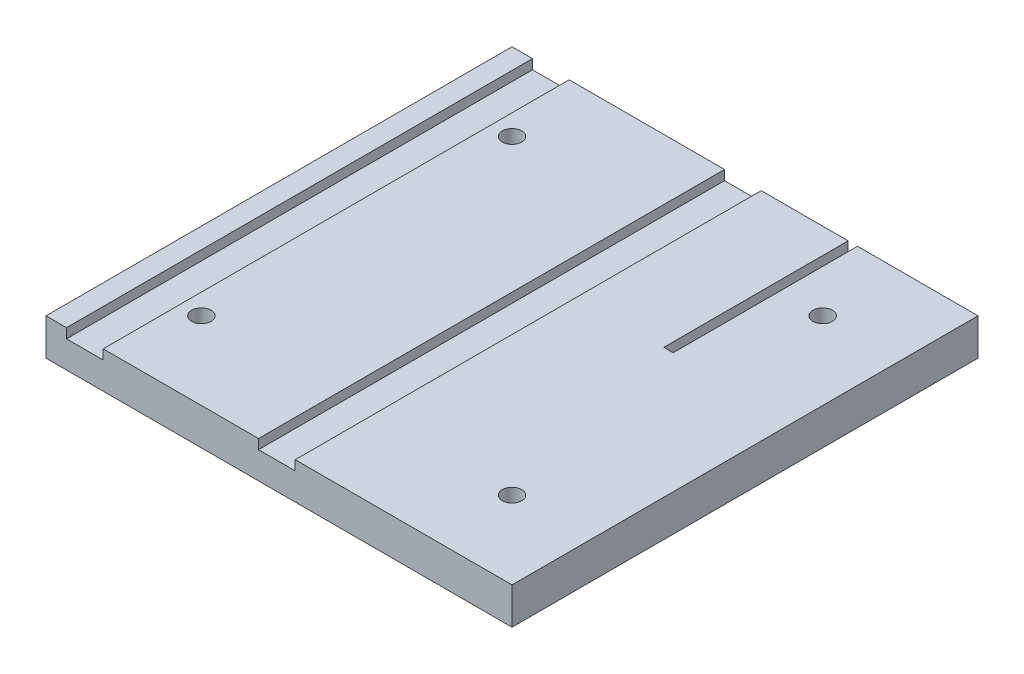
SolidWorks part; units mm, degrees
ref_plane "Front Plane" through (0, 0, 0) normal (0, 0, 1) x (1, 0, 0)
ref_plane "Top Plane" through (0, 0, 0) normal (0, 1, 0) x (1, 0, 0)
ref_plane "Right Plane" through (0, 0, 0) normal (1, 0, 0) x (0, 0, -1)
sketch "Sketch1" plane through (0, 0, 0) normal (0, 1, 0) x (1, 0, 0)
  line L1 (-76.2, 76.2) -> (76.2, 76.2)
  line L2 (-76.2, 76.2) -> (-76.2, -76.2)
  line L3 (-76.2, -76.2) -> (76.2, -76.2)
  line L4 (76.2, 76.2) -> (76.2, -76.2)
  line L5 (-76.2, 76.2) -> (76.2, -76.2) construction
  line L6 (-76.2, -76.2) -> (76.2, 76.2) construction
  circle A0 centre (-50.8, 50.8) radius 3.175
  circle A1 centre (50.8, 50.8) radius 3.175
  circle A2 centre (-50.8, -50.8) radius 3.175
  circle A3 centre (50.8, -50.8) radius 3.175
  point P0 (0, 0)
  dimension "D3" = 6.35
  dimension "D4" = 6.35
  dimension "D5" = 6.35
  dimension "D6" = 6.35
  dimension "D7" = 25.4
  dimension "D8" = 25.4
  dimension "D9" = 25.4
  dimension "D10" = 101.6
  dimension "D11" = 25.4
  dimension "D12" = 25.4
  dimension "D13" = 25.4
  dimension "D14" = 25.4
  dimension "D15" = 76.2
  dimension "D1" = 152.4
  dimension "D2" = 152.4
  dimension "D16" = 76.2
extrude "Boss-Extrude1" add sketch "Sketch1" along normal blind 12
sketch "Sketch2" plane through (0, 12, 0) normal (0, 1, 0) x (1, 0, 0)
  line L1 (-57.5, -76.2) -> (-69.5, -76.2)
  line L2 (-57.5, -76.2) -> (-57.5, 76.2)
  line L3 (-57.5, 76.2) -> (-69.5, 76.2)
  line L4 (-69.5, -76.2) -> (-69.5, 76.2)
  line L5 (-57.5, -76.2) -> (-69.5, 76.2) construction
  line L6 (-57.5, 76.2) -> (-69.5, -76.2) construction
  line L7 (-76.2, -76.2) -> (76.2, -76.2) construction
  line L9 (5.3, -76.2) -> (-6.7, -76.2)
  line L10 (5.3, -76.2) -> (5.3, 76.2)
  line L11 (5.3, 76.2) -> (-6.7, 76.2)
  line L12 (-6.7, -76.2) -> (-6.7, 76.2)
  line L13 (5.3, -76.2) -> (-6.7, 76.2) construction
  line L14 (5.3, 76.2) -> (-6.7, -76.2) construction
  line L15 (-76.2, 76.2) -> (-76.2, -76.2) construction
  line L17 (76.2, -76.2) -> (76.2, 76.2) construction
  line L18 (33.7325, 119.9745) -> (36.8088, 119.9745)
  line L19 (33.7325, 119.9745) -> (33.7325, 15.8925)
  line L20 (33.7325, 15.8925) -> (36.8088, 15.8925)
  line L21 (36.8088, 119.9745) -> (36.8088, 15.8925)
  line L22 (33.7325, 119.9745) -> (36.8088, 15.8925) construction
  line L23 (33.7325, 15.8925) -> (36.8088, 119.9745) construction
  point P0 (-63.5, 0)
  point P9 (-0.7, 0)
  point P14 (35.2707, 67.9335)
  dimension "D1" = 12.7
  dimension "D2" = 12
  dimension "D3" = 152.4
  dimension "D4" = 0
  dimension "D5" = 0
  dimension "D6" = 152.4
  dimension "D7" = 12
  dimension "D8" = 69.5
  dimension "D9" = 39.3912
extrude "Cut-Extrude1" cut sketch "Sketch2" against normal blind 3.175
